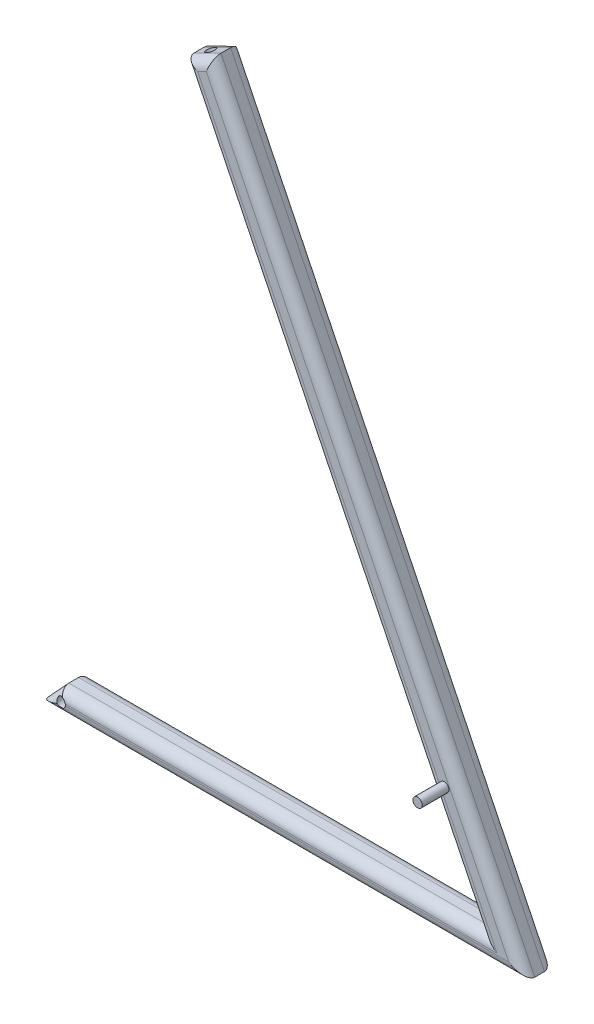
SolidWorks part; units mm, degrees
material "AA356.0-F"
ref_plane "Front Plane" through (0, 0, 0) normal (0, 0, 1) x (1, 0, 0)
ref_plane "Top Plane" through (0, 0, 0) normal (0, 1, 0) x (1, 0, 0)
ref_plane "Right Plane" through (0, 0, 0) normal (1, 0, 0) x (0, 0, -1)
sketch "Sketch1" plane through (0, 0, 0) normal (0, 0, 1) x (1, 0, 0)
  line L6 (-253.5187, -141.5797) -> (475.1092, -141.5797)
  line L7 (475.1092, -141.5797) -> (4.6879, 822.9269)
  line L8 (4.6879, 822.9269) -> (-35.3085, 803.4194)
  line L9 (-35.3085, 803.4194) -> (409.6382, -108.8566)
  line L10 (409.6382, -108.8566) -> (-223.3618, -108.8566)
  line L11 (-223.3618, -108.8566) -> (-253.5187, -141.5797)
  dimension "D1" = 64
  dimension "D2" = 728.6279
  dimension "D3" = 44.5
  dimension "D4" = 1015
  dimension "D5" = 633
  dimension "D6" = 44.5
extrude "Boss-Extrude1" add sketch "Sketch1" along normal blind 44.5
fillet "Fillet2" radius 15 12 edges at (93.1382, -108.8566, 44.5) (187.1649, 347.2814, 44.5) (-15.3103, 813.1732, 44.5) (239.8985, 340.6736, 44.5) (110.7952, -141.5797, 44.5) (-238.4402, -125.2181, 44.5) (110.7952, -141.5797, 0) (239.8985, 340.6736, 0) (-15.3103, 813.1732, 0) (187.1649, 347.2814, 0) (93.1382, -108.8566, 0) (-238.4402, -125.2181, 0)
sketch "Sketch2" plane through (-323.3368, 662.9386, 0) normal (-0.4384, 0.8988, 0) x (0.8988, 0.4384, 0)
  circle A0 centre (339.4702, -21.9136) radius 7
extrude "Cut-Extrude1" cut sketch "Sketch2" against normal blind 14
sketch "Sketch3" plane through (-66.5341, 61.3164, 0) normal (-0.7354, 0.6777, 0) x (0, 0, 1)
  circle A0 centre (22.3663, -255.5101) radius 7
extrude "Cut-Extrude2" cut sketch "Sketch3" against normal blind 14
sketch "Sketch4" plane through (0, -141.5797, 0) normal (0, -1, 0) x (-1, 0, 0)
  circle A0 centre (233.4195, -21.2015) radius 7
extrude "Cut-Extrude3" cut sketch "Sketch4" against normal blind 14
sketch "Sketch5" plane through (0, 0, 44.5) normal (0, 0, 1) x (1, 0, 0)
  circle A1 centre (-220.6491, -125.4271) radius 7
extrude "Cut-Extrude4" cut sketch "Sketch5" against normal through all
sketch "Sketch6" plane through (-66.5341, 61.3164, 0) normal (-0.7354, 0.6777, 0) x (0, 0, 1)
  line L1 (15, -231.4168) -> (29.5, -231.4168)
  line L2 (15, -231.4168) -> (15, -275.9168)
  line L3 (15, -275.9168) -> (29.5, -275.9168)
  line L4 (29.5, -231.4168) -> (29.5, -275.9168)
extrude "Cut-Extrude5" cut sketch "Sketch6" against normal through all
sketch "Sketch8" plane through (0, 0, 44.5) normal (0, 0, 1) x (1, 0, 0)
  line L0 (451.1042, -126.5797) -> (436.1934, -126.5797)
  line L1 (-213.7447, -126.5797) -> (451.1042, -126.5797) construction
  line L2 (436.1934, -126.5797) -> (433.6433, -123.8566)
  circle A0 centre (354.4285, 52.4167) radius 7
  point P8 (443.6488, -126.5797)
  line M6 (-15.251, 796.5131) -> (433.6433, -123.8566)
  dimension "D1" = 200
extrude "Boss-Extrude3" add sketch "Sketch8" along normal blind 40 contours A0 M6 | A0 M6
